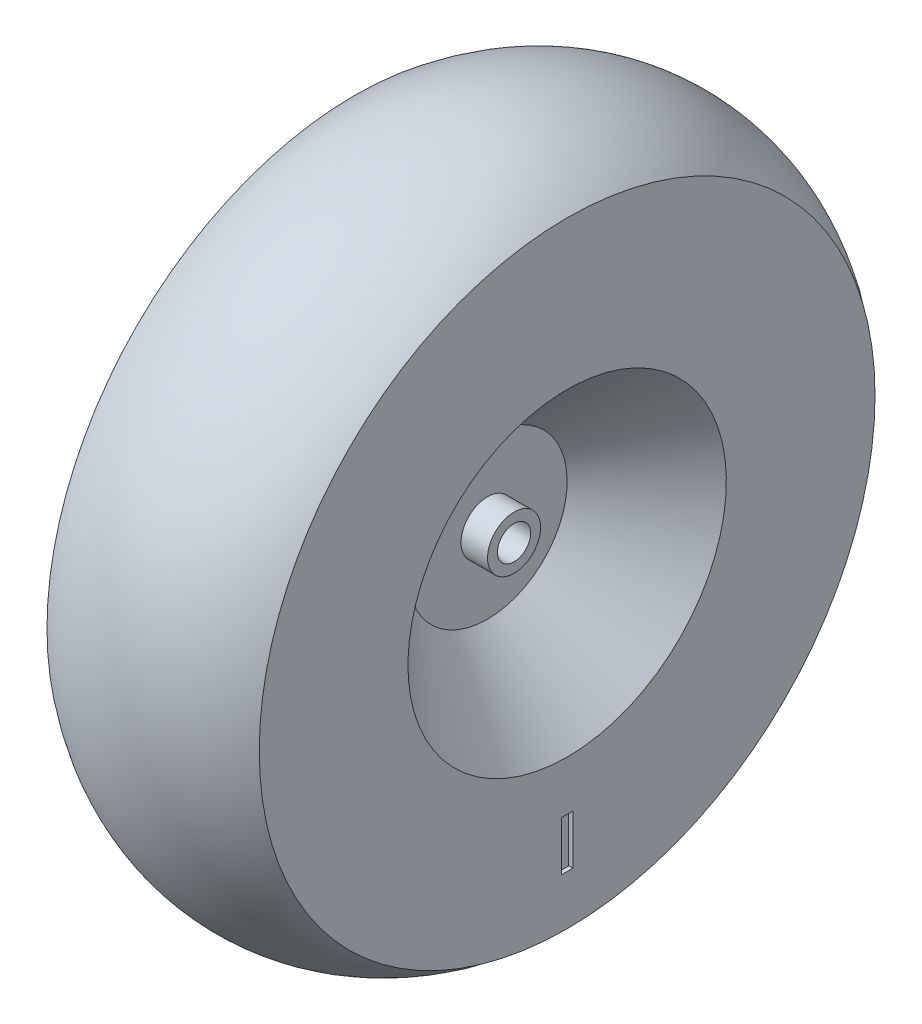
SolidWorks part; units mm, degrees
material "6061-T6 (SS)"
ref_plane "Front Plane" through (0, 0, 0) normal (0, 0, 1) x (1, 0, 0)
ref_plane "Top Plane" through (0, 0, 0) normal (0, 1, 0) x (1, 0, 0)
ref_plane "Right Plane" through (0, 0, 0) normal (1, 0, 0) x (0, 0, -1)
sketch "Sketch7" plane through (0, 0, 0) normal (0, 0, 1) x (1, 0, 0)
  line L4 (25.4, 7.9375) -> (25.4, 12.7)
  line L6 (12.7, 12.7) -> (25.4, 12.7)
  line L8 (12.7, 12.7) -> (12.7, 38.1)
  line L11 (-25.4, 0) -> (25.4, 0) construction
  line L12 (12.7, 38.1) -> (50.8, 76.2)
  line L13 (50.8, 76.2) -> (50.8, 147.3587)
  line L16 (25.4, 7.9375) -> (-25.4, 7.9375)
  line L44 (-12.7, 12.7) -> (12.7, 12.7) construction
  line L49 (-50.8, 147.3587) -> (50.8, 147.3587) construction
  line L53 (-50.8, 76.2) -> (-50.8, 147.3587)
  line L54 (-12.7, 38.1) -> (-50.8, 76.2)
  line L55 (-12.7, 12.7) -> (-12.7, 38.1)
  line L56 (-12.7, 12.7) -> (-25.4, 12.7)
  line L57 (-25.4, 7.9375) -> (-25.4, 12.7)
  ellipse E1 centre (0, 79.5701) end of major axis (0, -5.9598) minor radius 83.3088 (50.8, 147.3587) -> (-50.8, 147.3587) ccw
  point P5 (0, 0)
  point P6 (0, 12.7)
  point P8 (0, 147.3587)
  point P59 (50.8, 147.3587)
  dimension "D1" = 50.8
  dimension "D2" = 7.9375
  dimension "D3" = 101.6
  dimension "D4" = 76.2
  dimension "D5" = 165.1
  dimension "D6" = 45
  dimension "D8" = 25.4
  dimension "D9" = 12.7
revolve "Revolve6" add sketch "Sketch7" angle 360 about L11
sketch "Sketch8" plane through (50.8, 0, 0) normal (1, 0, 0) x (0, 0, -1)
  line L0 (0, -76.2) -> (0, -99.9196) construction
  line L1 (0, -123.6391) -> (0, -147.3587) construction
  line L2 (-2.7528, -123.6391) -> (2.7528, -123.6391)
  line L3 (-2.7528, -123.6391) -> (-2.7528, -99.9196)
  line L4 (-2.7528, -99.9196) -> (2.7528, -99.9196)
  line L5 (2.7528, -123.6391) -> (2.7528, -99.9196)
  line L6 (-2.7528, -123.6391) -> (2.7528, -99.9196) construction
  line L7 (-2.7528, -99.9196) -> (2.7528, -123.6391) construction
  circle A0 centre (0, 0) radius 76.2 construction
  circle A1 centre (0, 0) radius 147.3587 construction
  point P7 (0, -111.7793)
extrude "Cut-Extrude1" cut sketch "Sketch8" against normal blind 2
